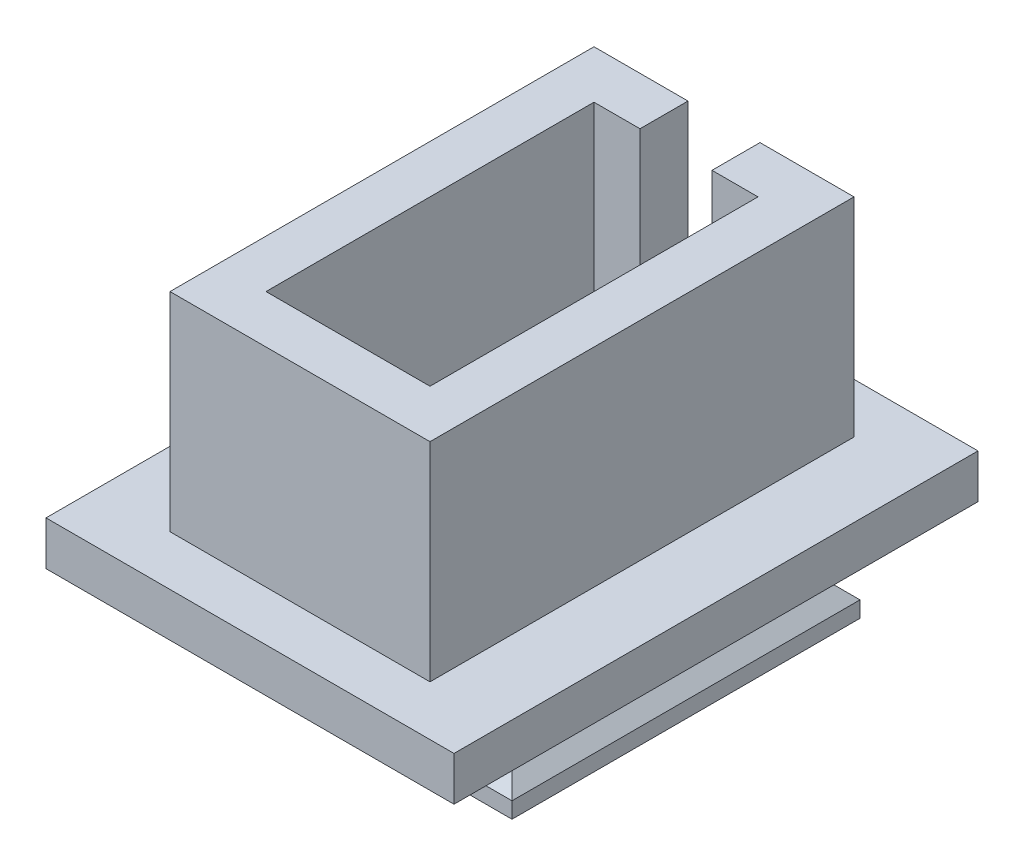
SolidWorks part; units mm, degrees
ref_plane "Front Plane" through (0, 0, 0) normal (0, 0, 1) x (1, 0, 0)
ref_plane "Top Plane" through (0, 0, 0) normal (0, 1, 0) x (1, 0, 0)
ref_plane "Right Plane" through (0, 0, 0) normal (1, 0, 0) x (0, 0, -1)
sketch "Sketch1" plane through (0, 0, 0) normal (0, 1, 0) x (1, 0, 0)
  line L1 (-27.7005, 18.3644) -> (15.7995, 18.3644)
  line L2 (-27.7005, 18.3644) -> (-27.7005, -25.1356)
  line L3 (-27.7005, -25.1356) -> (15.7995, -25.1356)
  line L4 (15.7995, 18.3644) -> (15.7995, -25.1356)
  dimension "D1" = 43.5
  dimension "D2" = 43.5
extrude "Boss-Extrude1" add sketch "Sketch1" along normal blind 2
sketch "Sketch2" plane through (0, 2, 0) normal (0, 1, 0) x (1, 0, 0)
  line L1 (-27.7005, 18.3644) -> (15.7995, 18.3644)
  line L2 (-27.7005, 18.3644) -> (-27.7005, -25.1356)
  line L3 (-27.7005, -25.1356) -> (15.7995, -25.1356)
  line L4 (15.7995, 18.3644) -> (15.7995, -25.1356)
extrude "Boss-Extrude3" add sketch "Sketch2" along normal blind 7 separate body
sketch "Sketch4" plane through (0, 9, 0) normal (0, 1, 0) x (1, 0, 0)
  line L0 (-20.7005, 11.3644) -> (-20.7005, -18.1356)
  line L1 (-27.7005, 18.3644) -> (15.7995, 18.3644)
  line L2 (-27.7005, 18.3644) -> (-27.7005, -25.1356)
  line L3 (-27.7005, -25.1356) -> (15.7995, -25.1356)
  line L4 (15.7995, 18.3644) -> (15.7995, -25.1356)
  line L5 (-20.7005, -18.1356) -> (8.7995, -18.1356)
  line L6 (8.7995, 11.3644) -> (8.7995, -18.1356)
  line L7 (-20.7005, 11.3644) -> (8.7995, 11.3644)
  dimension "D1" = 7
sketch "Sketch5" plane through (0, 0, 25.1356) normal (0, 0, 1) x (1, 0, 0)
  line L0 (-27.7005, 2) -> (-20.7005, 9)
  line L1 (-27.7005, 9) -> (-20.7005, 9)
  line L2 (-27.7005, 9) -> (-27.7005, 2)
  line L3 (15.7995, 9) -> (15.7995, 2)
  line L4 (15.7995, 2) -> (8.7995, 9)
  line L5 (-20.7005, 9) -> (-27.7005, 9)
  line L6 (-27.7005, 9) -> (15.7995, 9) construction
  line L7 (8.7995, 9) -> (15.7995, 9)
  line M4 (15.7995, 2) -> (15.7995, 9)
  line M5 (15.7995, 9) -> (-27.7005, 9)
  line M6 (-27.7005, 9) -> (-27.7005, 2)
  dimension "D1" = 7
  dimension "D2" = 7
extrude "Cut-Extrude1" cut sketch "Sketch5" against normal through all contours L4 M4 M5 | L0 M6 M5
sketch "Sketch6" plane through (15.7995, 0, 0) normal (1, 0, 0) x (0, 0, -1)
  line L0 (-25.1356, 2) -> (-25.1356, 9)
  line L1 (-25.1356, 9) -> (-18.1356, 9)
  line L2 (18.3644, 9) -> (-25.1356, 9) construction
  line L3 (-18.1356, 9) -> (-25.1356, 2)
  line L4 (18.3644, 2) -> (18.3644, 9)
  line L5 (18.3644, 9) -> (11.3644, 9)
  line L6 (11.3644, 9) -> (18.3644, 2)
  dimension "D1" = 7
  dimension "D2" = 7
extrude "Cut-Extrude2" cut sketch "Sketch6" against normal through all
sketch "Sketch7" plane through (0, 9, 0) normal (0, 1, 0) x (1, 0, 0)
  line L2 (19.5495, -36.1356) -> (-31.4505, -36.1356)
  line L3 (19.5495, -36.1356) -> (19.5495, 29.3644)
  line L4 (19.5495, 29.3644) -> (-31.4505, 29.3644)
  line L5 (-31.4505, -36.1356) -> (-31.4505, 29.3644)
  line L6 (19.5495, -36.1356) -> (-31.4505, 29.3644) construction
  line L7 (19.5495, 29.3644) -> (-31.4505, -36.1356) construction
  point P4 (-5.9505, -3.3856)
  dimension "D1" = 51
  dimension "D2" = 65.5
extrude "Boss-Extrude4" add sketch "Sketch7" along normal blind 5.5
sketch "Sketch8" plane through (0, 0, 0) normal (0, -1, 0) x (1, 0, 0)
  line L0 (-27.7005, 25.1356) -> (15.7995, -18.3644) construction
  line L1 (15.7995, -18.3644) -> (-27.7005, -18.3644) construction
  circle A0 centre (-5.9505, 3.3856) radius 3.25
  dimension "D1" = 6.5
sketch "Sketch9" plane through (0, 14.5, 0) normal (0, 1, 0) x (1, 0, 0)
  line L0 (-22.2005, -29.8856) -> (-22.2005, 23.1144)
  line L1 (-16.2005, -23.8856) -> (4.2995, -23.8856)
  line L2 (-16.2005, -23.8856) -> (-16.2005, 17.1144)
  line L3 (-16.2005, 17.1144) -> (4.2995, 17.1144)
  line L4 (4.2995, -23.8856) -> (4.2995, 17.1144)
  line L5 (-16.2005, -23.8856) -> (4.2995, 17.1144) construction
  line L6 (-16.2005, 17.1144) -> (4.2995, -23.8856) construction
  line L7 (-22.2005, 23.1144) -> (10.2995, 23.1144)
  line L8 (10.2995, -29.8856) -> (10.2995, 23.1144)
  line L9 (-22.2005, -29.8856) -> (10.2995, -29.8856)
  line L12 (-10.4505, 17.1144) -> (-10.4505, 23.1144)
  line L14 (-1.4505, 17.1144) -> (-1.4505, 23.1144)
  line L15 (-5.9505, 17.1144) -> (-3.2149, 23.1144) construction
  line L16 (-8.686, 23.1144) -> (-5.9505, 17.1144) construction
  point P0 (-5.9505, -3.3856)
  point P10 (-5.9505, 17.1144)
  dimension "D1" = 20.5
  dimension "D2" = 41
  dimension "D3" = 6
extrude "Boss-Extrude5" add sketch "Sketch9" along normal blind 26 contours L14 L3 L4 L1 L2 L12 L7 L0 L9 L8
